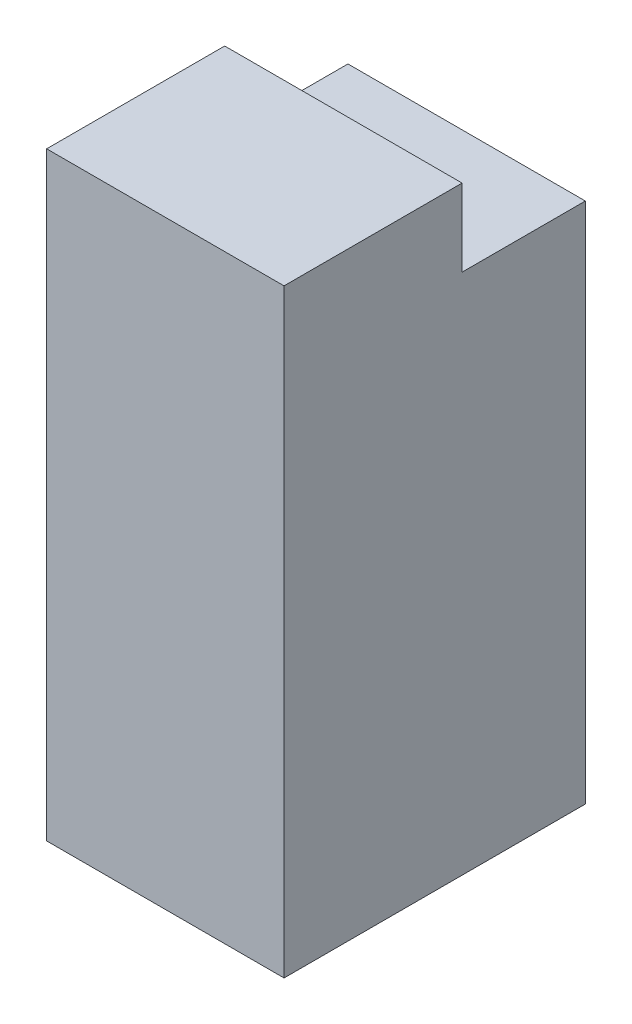
SolidWorks part; units mm, degrees
ref_plane "Front Plane" through (0, 0, 0) normal (0, 0, 1) x (1, 0, 0)
ref_plane "Top Plane" through (0, 0, 0) normal (0, 1, 0) x (1, 0, 0)
ref_plane "Right Plane" through (0, 0, 0) normal (1, 0, 0) x (0, 0, -1)
sketch "Sketch1" plane through (0, -4290, 0) normal (0, -1, 0) x (1, 0, 0)
  line L1 (-400, 300) -> (0, 300)
  line L2 (-400, 300) -> (-400, 0)
  line L3 (-400, 0) -> (0, 0)
  line L4 (0, 300) -> (0, 0)
  line L5 (-400, 300) -> (0, 0) construction
  line L6 (-400, 0) -> (0, 300) construction
  point P4 (-200, 150)
extrude "Boss-Extrude1" add sketch "Sketch1" along normal blind 1010
sketch "Sketch4" plane through (0, 0, 0) normal (0, 0, -1) x (-1, 0, 0)
  line L0 (400, -5300) -> (400, -4290) construction
  line L1 (0, -5300) -> (400, -5300)
  line L2 (0, -5300) -> (0, -4420)
  line L3 (0, -4420) -> (400, -4420)
  line L4 (400, -5300) -> (400, -4420)
  line L5 (0, -5300) -> (400, -4420) construction
  line L6 (0, -4420) -> (400, -5300) construction
  point P4 (200, -4860)
  dimension "D1" = 880
sketch "Sketch5" plane through (-400, 0, 0) normal (-1, 0, 0) x (0, 0, 1)
  line L0 (0, -4420) -> (-256.6345, -4420)
  line L1 (0, -5300) -> (0, -4420) construction
  line L2 (0, -5300) -> (0, -4420) construction
ref_plane "Plane1" through (0, 0, -207.6643) normal (0, 0, -1) x (-1, 0, 0)
sketch "Sketch2" plane through (0, 0, -207.6643) normal (0, 0, -1) x (-1, 0, 0)
  line L0 (0, -5300) -> (0, -4290) construction
  line L1 (400, -5300) -> (0, -5300)
  line L2 (400, -5300) -> (400, -4420)
  line L3 (400, -4420) -> (0, -4420)
  line L4 (0, -5300) -> (0, -4420)
  line L5 (400, -5300) -> (0, -4420) construction
  line L6 (400, -4420) -> (0, -5300) construction
  point P4 (200, -4860)
loft "Loft1" add profiles "Sketch2", "Sketch4"
